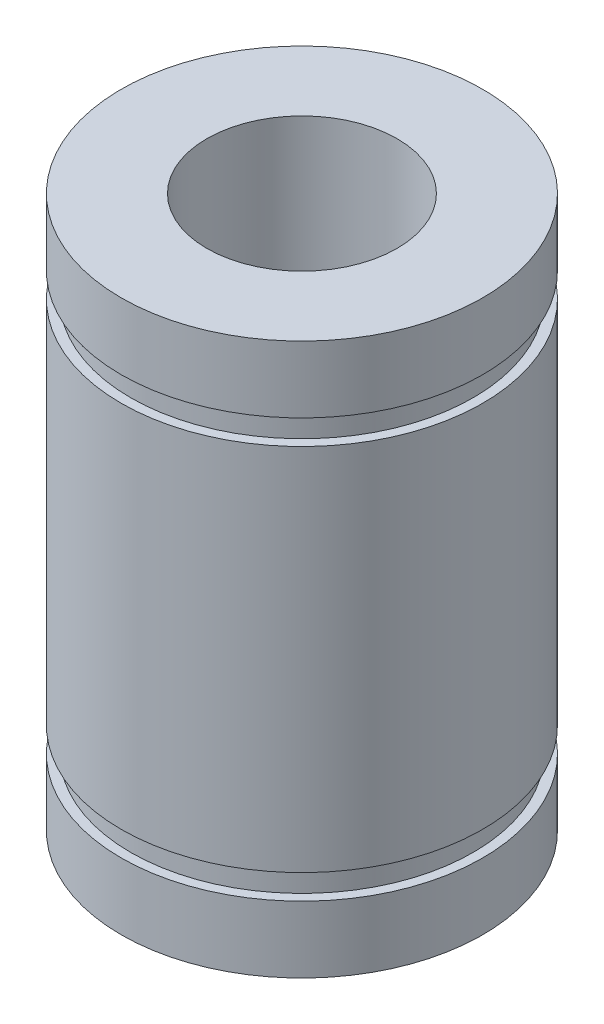
SolidWorks part; units mm, degrees
ref_plane "Front Plane" through (0, 0, 0) normal (0, 0, 1) x (1, 0, 0)
ref_plane "Top Plane" through (0, 0, 0) normal (0, 1, 0) x (1, 0, 0)
ref_plane "Right Plane" through (0, 0, 0) normal (1, 0, 0) x (0, 0, -1)
sketch "Sketch1" plane through (0, 0, 0) normal (0, 0, 1) x (1, 0, 0)
  line L0 (0, 46.0446) -> (0, -45.4182) construction
  line L1 (0, 0) -> (13.2112, 0) construction
  line L2 (5, 14.5) -> (9.5, 14.5)
  line L3 (5, 14.5) -> (5, -14.5)
  line L4 (5, -14.5) -> (9.5, -14.5)
  line L5 (9.5, 14.5) -> (9.5, 11)
  line L6 (9.5, 9.7) -> (9.5, -9.7)
  line L7 (9.5, 11) -> (9, 11)
  line L8 (9.5, -11) -> (9.5, -14.5)
  line L9 (9.5, 9.7) -> (9, 9.7)
  line L10 (9, 11) -> (9, 9.7)
  line L11 (9.5, -9.7) -> (9, -9.7)
  line L13 (9.5, -11) -> (9, -11)
  line L14 (9, -9.7) -> (9, -11)
  dimension "D1" = 10
  dimension "D2" = 19
  dimension "D3" = 29
  dimension "D4" = 22
  dimension "D5" = 1.3
  dimension "D6" = 1.3
  dimension "D7" = 18
revolve "Revolve1" add sketch "Sketch1" angle 360 about L0
equation "\"D6@Sketch1\"=\"D5@Sketch1\""
